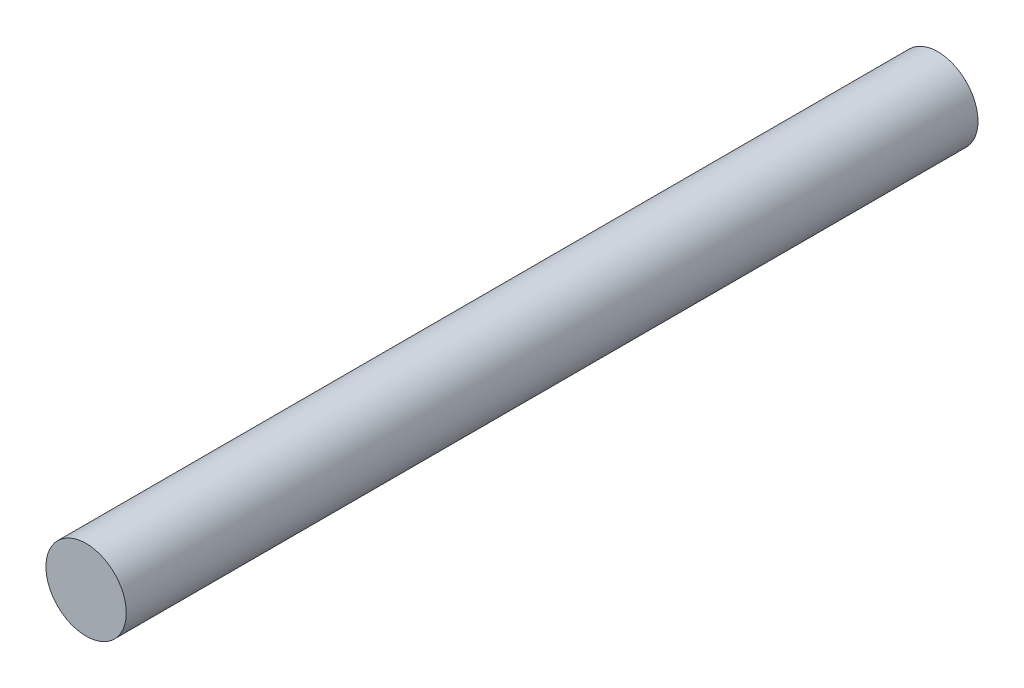
SolidWorks part; units mm, degrees
ref_plane "Front Plane" through (0, 0, 0) normal (0, 0, 1) x (1, 0, 0)
ref_plane "Top Plane" through (0, 0, 0) normal (0, 1, 0) x (1, 0, 0)
ref_plane "Right Plane" through (0, 0, 0) normal (1, 0, 0) x (0, 0, -1)
sketch "Sketch1" plane through (0, 0, 0) normal (0, 0, 1) x (1, 0, 0)
  circle A0 centre (0, 0) radius 2.5
  dimension "D1" = 5
extrude "Boss-Extrude1" add sketch "Sketch1" along normal blind 53
equation "\"f\"=53"
